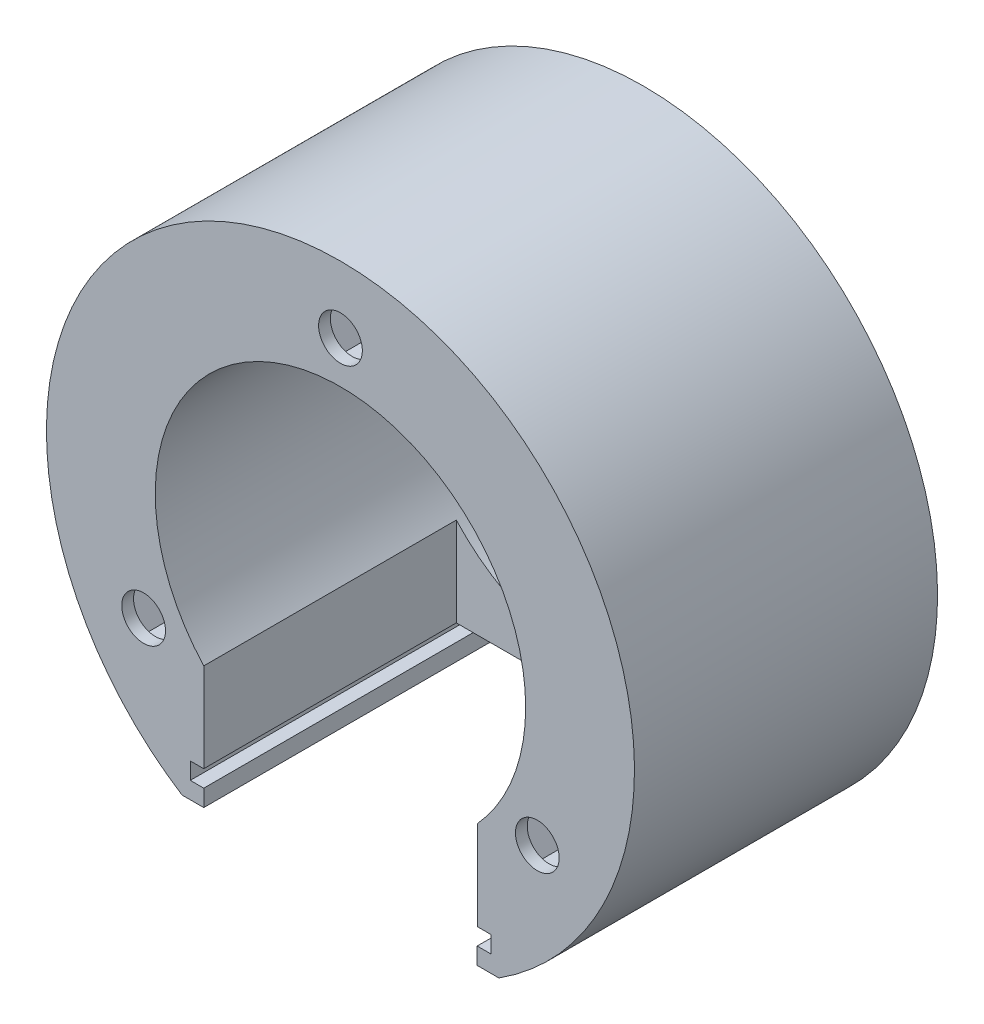
SolidWorks part; units mm, degrees
material "PET"
ref_plane "Front Plane" through (0, 0, 0) normal (0, 0, 1) x (1, 0, 0)
ref_plane "Top Plane" through (0, 0, 0) normal (0, 1, 0) x (1, 0, 0)
ref_plane "Right Plane" through (0, 0, 0) normal (1, 0, 0) x (0, 0, -1)
sketch "Sketch2" plane through (0, 0, 0) normal (0, 0, 1) x (1, 0, 0)
  circle A0 centre (0, 0) radius 17.4625
extrude "Boss-Extrude1" add sketch "Sketch2" along normal blind 18
sketch "Sketch13" plane through (0, 0, 18) normal (0, 0, 1) x (1, 0, 0)
  circle A0 centre (0, 13.5) radius 1.3
  circle A2 centre (11.6913, -6.75) radius 1.3
  circle A3 centre (-11.6913, -6.75) radius 1.3
  point P9 (0, 0)
  dimension "D1" = 3
  dimension "D2" = 13.5
extrude "Cut-Extrude6" cut sketch "Sketch13" against normal blind 15
sketch "Sketch16" plane through (0, 0, 18) normal (0, 0, 1) x (1, 0, 0)
  circle A0 centre (0, 0) radius 11
extrude "Cut-Extrude9" cut sketch "Sketch16" against normal blind 15
sketch "Sketch20" plane through (5.9573, 0, -11.0843) normal (0, 1, 0) x (0, 0, 1)
  line L0 (16.5293, -11.0218) -> (16.5293, -6.9068)
  line L1 (23.6393, -11.0218) -> (23.6393, -0.8118)
  line L2 (14.9293, -6.9068) -> (14.9293, -4.9268)
  line L3 (14.9293, -6.9068) -> (16.5293, -6.9068)
  line L4 (14.9293, -4.9268) -> (16.5293, -4.9268)
  line L5 (16.5293, -4.9268) -> (16.5293, -0.8118)
  line L6 (16.5293, -0.8118) -> (18.0543, -0.8118)
  line L7 (18.0543, -0.8118) -> (18.0543, 1.0282)
  line L8 (22.1143, -0.8118) -> (22.1143, 1.0282)
  line L9 (18.0543, 1.0282) -> (22.1143, 1.0282)
  line L10 (18.0543, -12.8618) -> (18.0543, -11.0218)
  line L11 (18.0543, -12.8618) -> (22.1143, -12.8618)
  line L12 (22.1143, -12.8618) -> (22.1143, -11.0218)
  line L13 (23.6393, -0.8118) -> (22.1143, -0.8118)
  line L14 (23.6393, -11.0218) -> (22.1143, -11.0218)
  line L15 (16.5293, -11.0218) -> (18.0543, -11.0218)
  line L16 (29.0843, -9.7935) -> (23.6393, -9.7935) construction
  line L18 (29.0843, -23.4198) -> (29.0843, 11.5052) construction
  line L19 (16.5293, -9.7935) -> (11.0843, -9.7935) construction
  line L20 (11.0843, 11.5052) -> (11.0843, -23.4198) construction
  dimension "D2" = 4.06
  dimension "D3" = 10.21
  dimension "D4" = 13.89
  dimension "D5" = 1.98
  dimension "D6" = 8.71
  dimension "D7" = 7.11
extrude "Cut-Extrude11" cut sketch "Sketch20" against normal blind 22
sketch "Sketch21" plane through (0, 0, 18) normal (0, 0, 1) x (1, 0, 0)
  line L1 (-8.125, -15.46) -> (8.125, -15.46)
  line L2 (-8.125, -15.46) -> (-8.125, -18.2444)
  line L3 (-8.125, -18.2444) -> (8.125, -18.2444)
  line L4 (8.125, -15.46) -> (8.125, -18.2444)
  dimension "D1" = 16.25
  dimension "D2" = 8.125
  dimension "D3" = 15.46
extrude "Cut-Extrude12" cut sketch "Sketch21" against normal through all
sketch "Sketch24" plane through (0, 0, 18) normal (0, 0, 1) x (1, 0, 0)
  line L0 (-8.1196, -6.7586) -> (8.1304, -6.7586)
  line L1 (-8.1196, -6.7586) -> (-8.1196, -13.46)
  line L2 (-8.1196, -13.46) -> (8.1304, -13.46)
  line L3 (8.1304, -6.7586) -> (8.1304, -13.46)
  dimension "D1" = 16.25
extrude "Cut-Extrude13" cut sketch "Sketch24" against normal up to surface (15 mm away) up to face at (11, 0, 3)
sketch "Sketch26" plane through (0, 0, 18) normal (0, 0, 1) x (1, 0, 0)
  line L4 (-8.1196, -13.71) -> (-8.1196, -15.46)
  line L5 (-8.1196, -15.46) -> (8.1196, -15.46)
  line L6 (8.1196, -15.46) -> (8.1196, -13.71)
  line L14 (-8.9196, -13.71) -> (-8.1196, -13.71)
  line L17 (8.9304, -13.71) -> (8.1196, -13.71)
  line L18 (-8.9196, -13.71) -> (-8.9196, -12.71)
  line L19 (-8.9196, -12.71) -> (8.9304, -12.71)
  line L20 (8.9304, -12.71) -> (8.9304, -13.71)
  dimension "D1" = 1
  dimension "D2" = 1
  dimension "D3" = 1.75
extrude "Cut-Extrude14" cut sketch "Sketch26" against normal blind 17
sketch "Sketch27" plane through (0, 0, 18) normal (0, 0, 1) x (1, 0, 0)
  line L0 (-8.1196, -15.46) -> (8.1196, -15.46) construction
  line L1 (-9.4104, -14.71) -> (9.4104, -14.71)
  line L2 (-9.4104, -14.71) -> (-9.4104, -15.46)
  line L3 (-9.4104, -15.46) -> (9.4104, -15.46)
  line L4 (9.4104, -14.71) -> (9.4104, -15.46)
  arc A0 (8.1196, -15.46) -> (-8.1196, -15.46) centre (0, 0) ccw construction
  dimension "D2" = 0.75
extrude "Cut-Extrude15" cut sketch "Sketch27" against normal through all
sketch "Sketch28" plane through (0, 0, 3) normal (0, 0, 1) x (1, 0, 0)
  line L43 (2.3094, 13.5) -> (1.1547, 15.5)
  line L44 (1.1547, 15.5) -> (-1.1547, 15.5)
  line L45 (-1.1547, 15.5) -> (-2.3094, 13.5)
  line L46 (-2.3094, 13.5) -> (-1.1547, 11.5)
  line L47 (-1.1547, 11.5) -> (1.1547, 11.5)
  line L48 (1.1547, 11.5) -> (2.3094, 13.5)
  line L49 (-9.3819, -6.75) -> (-10.5366, -4.75)
  line L50 (-10.5366, -4.75) -> (-12.846, -4.75)
  line L51 (-12.846, -4.75) -> (-14.0007, -6.75)
  line L52 (-14.0007, -6.75) -> (-12.846, -8.75)
  line L53 (-12.846, -8.75) -> (-10.5366, -8.75)
  line L54 (-10.5366, -8.75) -> (-9.3819, -6.75)
  line L55 (14.0007, -6.75) -> (12.846, -4.75)
  line L56 (12.846, -4.75) -> (10.5366, -4.75)
  line L57 (10.5366, -4.75) -> (9.3819, -6.75)
  line L58 (9.3819, -6.75) -> (10.5366, -8.75)
  line L59 (10.5366, -8.75) -> (12.846, -8.75)
  line L60 (12.846, -8.75) -> (14.0007, -6.75)
  circle A0 centre (0, 13.5) radius 2 construction
  circle A1 centre (-11.6913, -6.75) radius 2 construction
  circle A2 centre (11.6913, -6.75) radius 2 construction
extrude "Cut-Extrude16" cut sketch "Sketch28" against normal blind 1.8 from offset 14.3
sketch "Sketch29" plane through (0, 0, 3) normal (0, 0, 1) x (1, 0, 0)
  circle A0 centre (0, 0) radius 11
extrude "Cut-Extrude17" cut sketch "Sketch29" against normal blind 1.75
